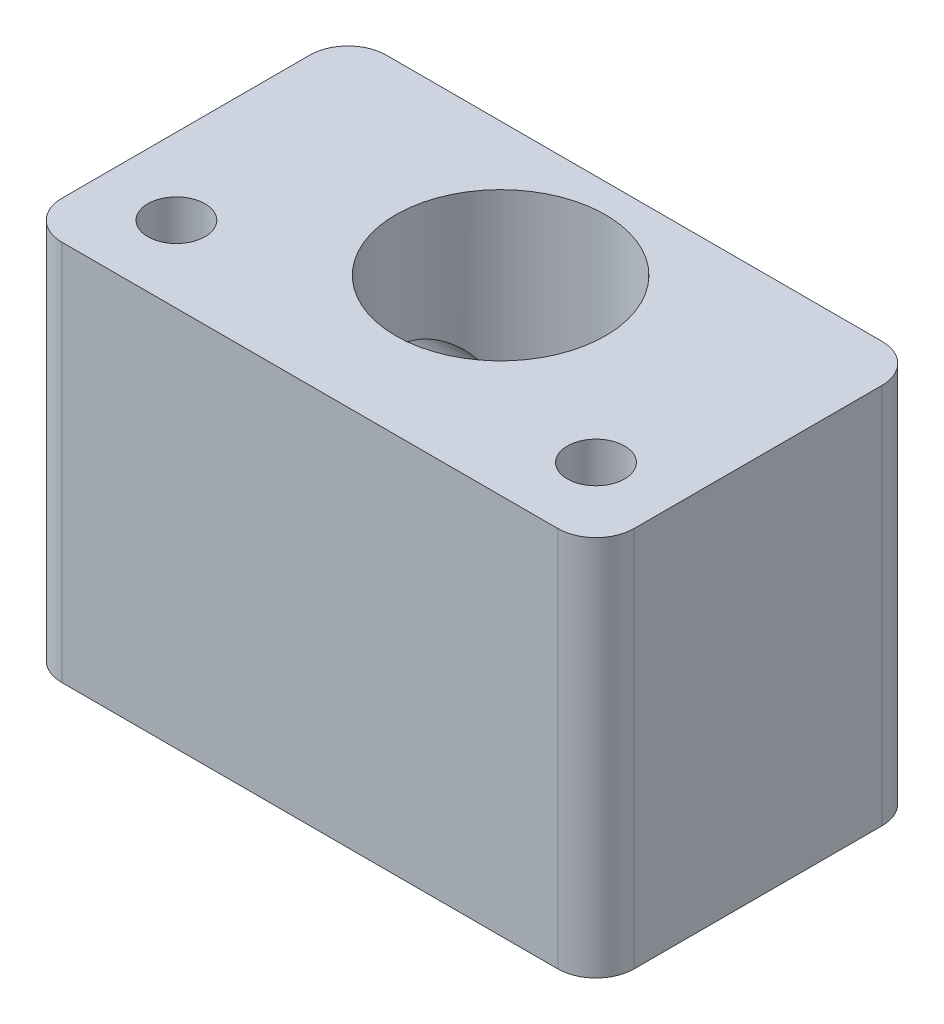
SolidWorks part; units mm, degrees
ref_plane "前视基准面" through (0, 0, 0) normal (0, 0, 1) x (1, 0, 0)
ref_plane "上视基准面" through (0, 0, 0) normal (0, 1, 0) x (1, 0, 0)
ref_plane "右视基准面" through (0, 0, 0) normal (1, 0, 0) x (0, 0, -1)
sketch "草图1" plane through (0, 0, 0) normal (0, 1, 0) x (1, 0, 0)
  line L0 (0, 0) -> (15, 0) construction
  line L1 (-15, -8.5) -> (15, -8.5)
  line L2 (-15, -8.5) -> (-15, 8.5)
  line L3 (-15, 8.5) -> (15, 8.5)
  line L4 (15, -8.5) -> (15, 8.5)
  line L5 (-15, -8.5) -> (15, 8.5) construction
  line L6 (-15, 8.5) -> (15, -8.5) construction
  line L7 (0, -2.2065) -> (0, 7.7935) construction
  circle A3 centre (-11, -4.5) radius 1.5
  circle A4 centre (11, -4.5) radius 1.5
  circle A5 centre (0, 1.5) radius 5.5
  point P0 (0, 0.9325)
  dimension "D3" = 4
  dimension "D4" = 4
  dimension "D5" = 3
  dimension "D6" = 11
  dimension "D7" = 10
  dimension "D1" = 30
  dimension "D2" = 17
extrude "凸台-拉伸1" add sketch "草图1" along normal blind 20
sketch "草图2" plane through (-15, 0, 0) normal (-1, 0, 0) x (0, 0, 1)
  line L0 (-8.5, 10) -> (8.5, 10) construction
  line L1 (-8.5, 20) -> (-8.5, 0) construction
  line L2 (8.5, 20) -> (8.5, 0) construction
  line L3 (4, 20) -> (-7, 20) construction
  line L4 (4, 20) -> (-7, 20) construction
  line L5 (-1.5, 20) -> (-1.5, 0) construction
  line L6 (-8.5, 0) -> (8.5, 0) construction
  circle A0 centre (-1.5, 10) radius 4
  dimension "D1" = 8
extrude "切除-拉伸1" cut sketch "草图2" against normal up to next
fillet "圆角1" radius 2 4 edges at (15, 10, -8.5) (15, 10, 8.5) (-15, 10, 8.5) (-15, 10, -8.5)
